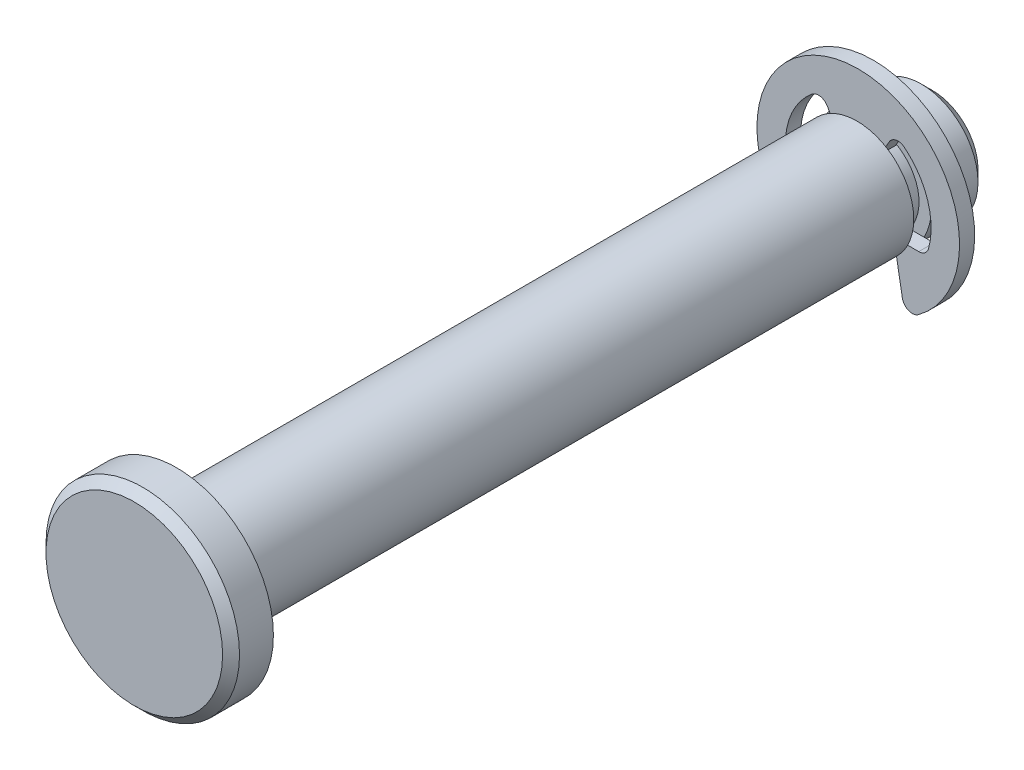
SolidWorks part; units mm, degrees
ref_plane "Front" through (0, 0, 0) normal (0, 0, 1) x (1, 0, 0)
ref_plane "Top" through (0, 0, 0) normal (0, 1, 0) x (1, 0, 0)
ref_plane "Right" through (0, 0, 0) normal (1, 0, 0) x (0, 0, -1)
sketch "Sketch2" plane through (0, 0, 0) normal (0, 0, 1) x (1, 0, 0)
  circle A0 centre (0, 0) radius 2.3813
  point P3 (0, 2.3813)
  point P4 (0, -2.3813)
  dimension "dia" = 4.7625
extrude "Extrude1" add sketch "Sketch2" along normal mid plane 31.75
sketch "Sketch3" plane through (0, 0, 0) normal (1, 0, 0) x (0, 0, -1)
  line L0 (15.875, 2.3813) -> (-15.875, 2.3813) construction
  line L1 (12.7, 2.3812) -> (13.4366, 2.3813)
  line L2 (12.7, 2.3812) -> (12.7, 1.8669)
  line L3 (12.7, 1.8669) -> (13.4366, 1.8669)
  line L4 (13.4366, 2.3813) -> (13.4366, 1.8669)
  line L5 (-15.875, 2.3813) -> (-15.875, -2.3813) construction
  line L10 (13.4366, 1.8669) -> (13.4366, -1.8669) construction
  point P11 (13.4366, 0)
  point P14 (13.0683, 2.3813)
  dimension "groove wd" = 0.7366
  dimension "groove dia" = 3.7338
  dimension "usable lg" = 28.575
revolve "Cut-Revolve1" cut sketch "Sketch3" angle 360 about axis through (0, 0, 15.875) along (0, 0, -1)
sketch "Sketch8" plane through (0, 0, 15.875) normal (0, 0, 1) x (1, 0, 0)
  circle A0 centre (0, 0) radius 4.064
  dimension "head dia" = 8.128
extrude "Extrude6" add sketch "Sketch8" along normal blind 1.778
chamfer "Chamfer2" distance 0.3556 angle 45 1 edges at (4.064, 0, 17.653)
ref_plane "Plane1" through (0, 0, -13.0683) normal (0, 0, 1) x (1, 0, 0)
sketch "Sketch4" plane through (0, 0, -13.0683) normal (0, 0, 1) x (1, 0, 0)
  line L0 (0, 1.8669) -> (0, -1.8669) construction
  circle A0 centre (0, 0) radius 4.2545
  circle A1 centre (0, 0) radius 1.8669
  dimension "ring dia" = 8.509
extrude "Extrude2" add sketch "Sketch4" along normal mid plane 0.635 separate body
sketch "Sketch5" plane through (0, 0, 0) normal (0, 0, 1) x (1, 0, 0)
  line L0 (0, 4.2545) -> (0, 1.8669) construction
  line L1 (-1.5304, 2.6506) -> (0, 0)
  line L2 (-2.8484, -1.1201) -> (-1.4935, -1.1201)
  line L3 (0, 0) -> (1.5304, 2.6506)
  line L4 (-1.4935, -1.1201) -> (-1.9617, -3.7753)
  line L5 (1.4935, -1.1201) -> (1.9617, -3.7753)
  line L6 (1.4935, -1.1201) -> (2.8484, -1.1201)
  arc A0 (-1.5304, 2.6506) -> (-2.8484, -1.1201) centre (0, 0) ccw
  circle A1 centre (0, 0) radius 4.2545 construction
  circle A2 centre (0, 0) radius 1.8669 construction
  arc A3 (2.8484, -1.1201) -> (1.5304, 2.6506) centre (0, 0) ccw
  arc A4 (-1.9617, -3.7753) -> (1.9617, -3.7753) centre (0, 0) ccw
  circle A5 centre (0, 0) radius 1.8669 construction
  point P10 (0, 3.0607)
  dimension "D1" = 30
  dimension "D2" = 10
  dimension "D3" = 1.1201
extrude "Extrude4" cut sketch "Sketch5" against normal through all
sketch "Sketch6" plane through (0, 0, -12.7508) normal (0, 0, 1) x (1, 0, 0)
  line L0 (-0.9335, 1.6168) -> (0.9335, 1.6168)
  circle A0 centre (0, 0) radius 1.8669 construction
  arc A1 (0.9335, 1.6168) -> (-0.9335, 1.6168) centre (0, 0) ccw
extrude "Extrude5" add sketch "Sketch6" against normal up to surface (0.635 mm away) up to face at (0, 0.5273, -13.3858)
fillet "Fillet1" radius 0.4254 6 edges at (1.9617, -3.7753, -13.0683) (-1.9617, -3.7753, -13.0683) (2.8484, -1.1201, -13.0683) (1.5304, 2.6506, -13.0683) (-1.5304, 2.6506, -13.0683) (-2.8484, -1.1201, -13.0683)
chamfer "Chamfer1" distance 0.4763 angle 45 1 edges at (2.3813, 0, -15.875)
sketch "Sketch7" plane through (0, 0, 0) normal (1, 0, 0) x (0, 0, -1)
  line L0 (13.3858, 4.2545) -> (12.7508, 4.2545) construction
  line L1 (15.875, -2.3813) -> (15.875, 2.3813) construction
  line L2 (12.7508, -3.5079) -> (13.3858, -3.5079) construction
  line L3 (-17.653, 3.7084) -> (-17.653, -3.7084) construction
  point P0 (13.4366, -3.5079)
  point P1 (15.875, 2.3813)
  point P2 (-17.653, 4.064)
  point P6 (12.7, 4.2545)
  point P7 (15.875, -2.3813)
  point P12 (-15.875, 4.064)
  point P16 (12.7, -3.5079)
equation "\"D1@Chamfer1\" = \"dia@Sketch2\" * .1"
equation "\"D1@Fillet1\" = \"ring dia@Sketch4\" * .05"
equation "\"D3@Sketch5\" = \"groove dia@Sketch3\" * .3"
equation "\"D1@Chamfer2\" = \"head ht@Extrude6\" * .2"
